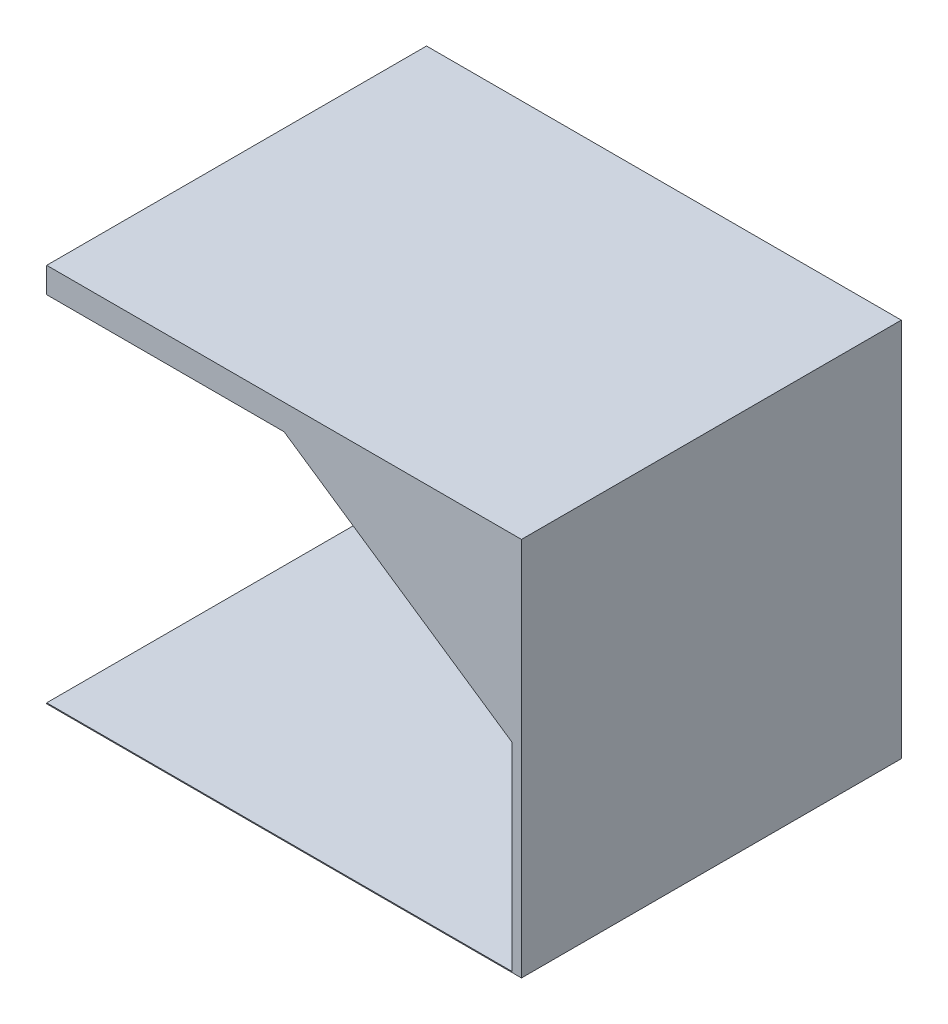
SolidWorks part; units mm, degrees
ref_plane "Front Plane" through (0, 0, 0) normal (0, 0, 1) x (1, 0, 0)
ref_plane "Top Plane" through (0, 0, 0) normal (0, 1, 0) x (1, 0, 0)
ref_plane "Right Plane" through (0, 0, 0) normal (1, 0, 0) x (0, 0, -1)
sketch "Sketch1" plane through (0, 0, 0) normal (0, 0, 1) x (1, 0, 0)
  line L0 (-1599.1508, 0) -> (1757.5573, 0) construction
  line L1 (0, 899.5223) -> (0, -922.1518) construction
  line L3 (1250, -1000) -> (-1250, -1000)
  line L4 (1250, -1000) -> (1250, 1000)
  line L5 (1250, 1000) -> (-1250, 1000)
  line L6 (-1250, -1000) -> (-1250, 1000)
  line L7 (1250, -1000) -> (-1250, 1000) construction
  line L8 (1250, 1000) -> (-1250, -1000) construction
  point P5 (0, 0)
  dimension "D1" = 2500
  dimension "D2" = 2000
extrude "Boss-Extrude1" add sketch "Sketch1" along normal blind 2000
sketch "Sketch2" plane through (0, 0, 2000) normal (0, 0, 1) x (1, 0, 0)
  line L1 (0, 865.901) -> (-1250, 865.901)
  line L2 (-1250, -1000) -> (1250, -1000) construction
  line L3 (-950, -995) -> (-1250, -995)
  line L5 (0, 865.901) -> (1200, 50.5007)
  line L6 (1200, 50.5007) -> (1200, -995)
  line L7 (0, 334.2162) -> (0, -1116.6034) construction
  line L8 (-1250, 1000) -> (-1250, -1000) construction
  line L9 (-950, -995) -> (1200, -995)
  line L10 (-1250, -995) -> (-1250, 865.901)
  line L11 (1250, -1000) -> (1250, 1000) construction
  dimension "D1" = 50
  dimension "D3" = 5
extrude "Cut-Extrude4" cut sketch "Sketch2" against normal blind 1995 and the other way through all
sketch "Sketch3" plane through (402.5256, 592.3847, 0) normal (-0.562, -0.8271, 0) x (0.8271, -0.562, 0)
  line L0 (238.7498, 5) -> (238.7498, 2000) construction
  line L1 (-486.66, 5) -> (964.1596, 5) construction
  line L2 (964.1596, 2000) -> (-486.66, 2000) construction
  line L3 (-486.66, 1500) -> (964.1596, 1500) construction
  line L4 (-486.66, 2000) -> (-486.66, 5) construction
  line L5 (964.1596, 2000) -> (964.1596, 5) construction
  line L6 (-486.66, 1000) -> (964.1596, 1000) construction
  line L7 (-486.66, 500) -> (964.1596, 500) construction
  circle A0 centre (238.7498, 1500) radius 100
  circle A1 centre (238.7498, 1002.5) radius 100
  circle A2 centre (238.7498, 500) radius 100
  dimension "D1" = 500
  dimension "D2" = 500
  dimension "D3" = 500
  dimension "D4" = 495
extrude "Cut-Extrude5" cut sketch "Sketch3" against normal blind 20
